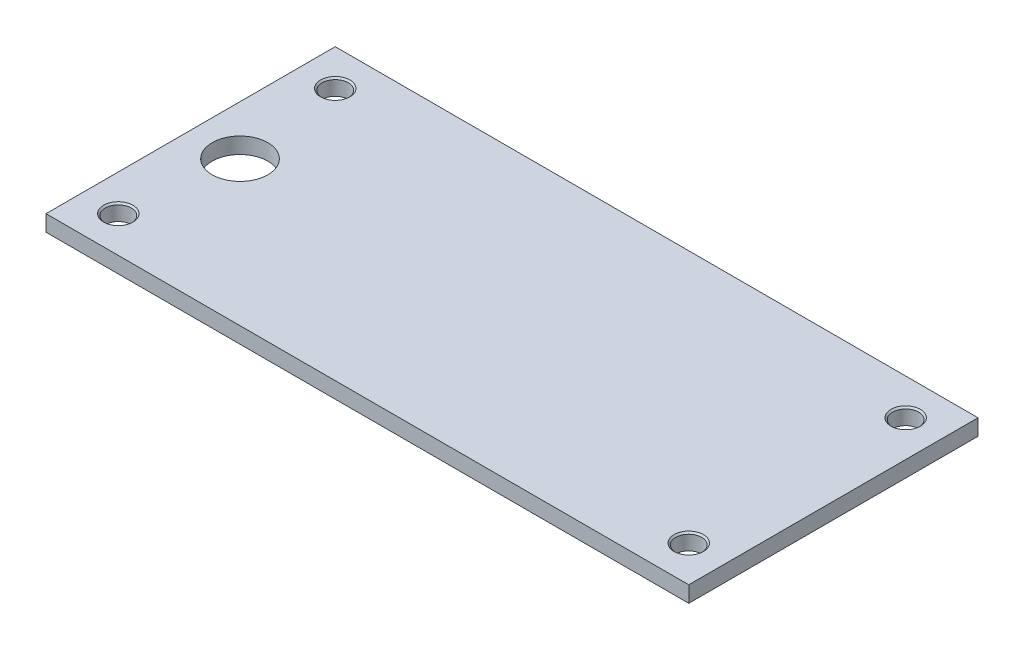
SolidWorks part; units mm, degrees
ref_plane "Front Plane" through (0, 0, 0) normal (0, 0, 1) x (1, 0, 0)
ref_plane "Top Plane" through (0, 0, 0) normal (0, 1, 0) x (1, 0, 0)
ref_plane "Right Plane" through (0, 0, 0) normal (1, 0, 0) x (0, 0, -1)
sketch "Sketch1" plane through (0, 0, 0) normal (0, 1, 0) x (1, 0, 0)
  line L1 (-127, -57.15) -> (127, -57.15)
  line L2 (-127, -57.15) -> (-127, 57.15)
  line L3 (-127, 57.15) -> (127, 57.15)
  line L4 (127, -57.15) -> (127, 57.15)
  line L5 (-127, -57.15) -> (127, 57.15) construction
  line L6 (-127, 57.15) -> (127, -57.15) construction
  point P0 (0, 0)
  dimension "D1" = 254
  dimension "D2" = 114.3
extrude "Boss-Extrude1" add sketch "Sketch1" along normal blind 6.35
sketch "Sketch2" plane through (0, 6.35, 0) normal (0, 1, 0) x (1, 0, 0)
  line L0 (127, 0) -> (-127, 0) construction
  line L1 (-127, 57.15) -> (-127, -57.15) construction
  circle A0 centre (-107.475, 0) radius 11
  dimension "D1" = 22
  dimension "D2" = 19.525
extrude "Cut-Extrude1" cut sketch "Sketch2" against normal through all contours A0
sketch "Sketch3" plane through (0, 6.35, 0) normal (0, 1, 0) x (1, 0, 0)
  point P0 (112.7125, 42.8625)
  point P1 (112.7125, -42.8675)
  point P3 (-112.7175, -42.8675)
  point P5 (-112.7175, 42.8625)
hole_wizard "3/8 Clearance Hole1" positions "Sketch3" profile "Sketch4" hole size "3/8" standard "ANSI Inch" end condition through all
sketch "Sketch4" plane through (112.7125, 6.35, -42.8625) normal (1, 0, 0) x (0, 0, 1)
  line L0 (0, 0) -> (0, 6.35)
  line L1 (0, 6.35) -> (5.1587, 6.35)
  line L2 (5.1587, 6.35) -> (5.1587, 0.635)
  line L3 (5.1587, 0.635) -> (5.7937, 0)
  line L5 (5.7937, 0) -> (0, 0)
  line L6 (-5.1587, 0.635) -> (-5.7937, 0) construction
  line L11 (0, -6.35) -> (0, 107.95) construction
  dimension "Thru Hole Dia." = 10.3175
  dimension "Thru Hole Depth" = 6.35
  dimension "Near C'Sink Dia." = 11.5875
  dimension "Near C'Sink Angle" = 90
